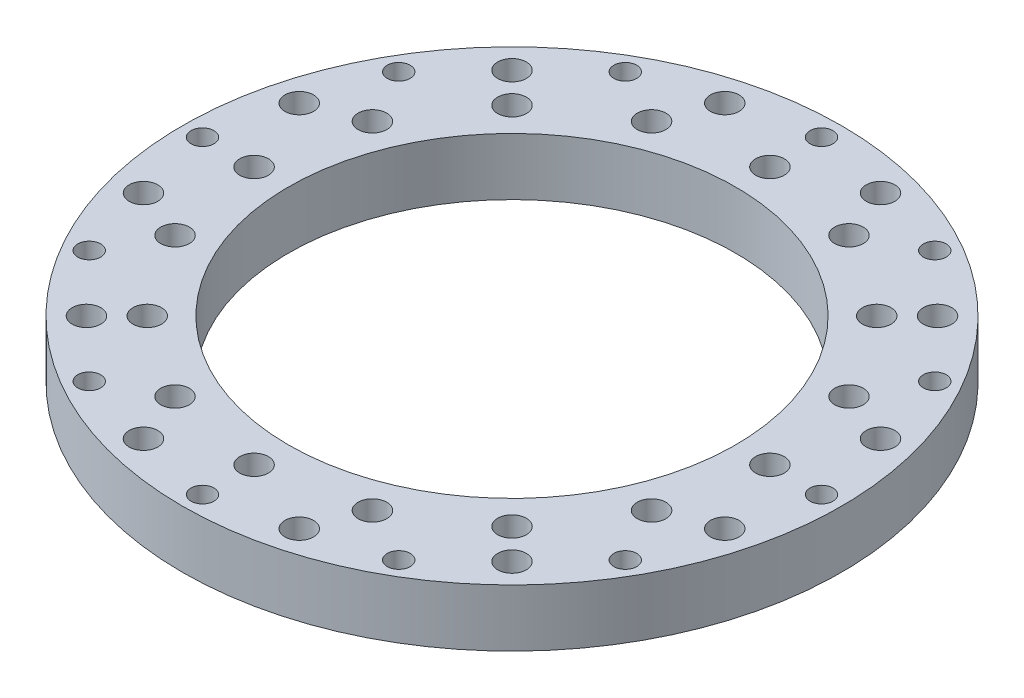
SolidWorks part; units mm, degrees
ref_plane "Front Plane" through (0, 0, 0) normal (0, 0, 1) x (1, 0, 0)
ref_plane "Top Plane" through (0, 0, 0) normal (0, 1, 0) x (1, 0, 0)
ref_plane "Right Plane" through (0, 0, 0) normal (1, 0, 0) x (0, 0, -1)
sketch "Sketch1" plane through (0, 0, 0) normal (0, 1, 0) x (1, 0, 0)
  line L0 (0, 0) -> (0, 52.5) construction
  line L1 (0, 0) -> (13.588, 50.7111) construction
  circle A12 centre (0, 0) radius 39
  circle A13 centre (0, 0) radius 57.5
  circle A14 centre (0, 0) radius 54 construction
  circle A15 centre (0, 54) radius 2
  circle A16 centre (27, 46.7654) radius 2
  circle A17 centre (46.7654, 27) radius 2
  circle A18 centre (54, 0) radius 2
  circle A19 centre (46.7654, -27) radius 2
  circle A20 centre (27, -46.7654) radius 2
  circle A21 centre (0, -54) radius 2
  circle A22 centre (-27, -46.7654) radius 2
  circle A23 centre (-46.7654, -27) radius 2
  circle A24 centre (-54, 0) radius 2
  circle A25 centre (-46.7654, 27) radius 2
  circle A26 centre (-27, 46.7654) radius 2
  circle A27 centre (0, 0) radius 52.5 construction
  circle A34 centre (13.588, 50.7111) radius 2.5
  circle A35 centre (37.1231, 37.1231) radius 2.5
  circle A36 centre (50.7111, 13.588) radius 2.5
  circle A37 centre (50.7111, -13.588) radius 2.5
  circle A38 centre (37.1231, -37.1231) radius 2.5
  circle A39 centre (13.588, -50.7111) radius 2.5
  circle A40 centre (-13.588, -50.7111) radius 2.5
  circle A41 centre (-37.1231, -37.1231) radius 2.5
  circle A42 centre (-50.7111, -13.588) radius 2.5
  circle A43 centre (-50.7111, 13.588) radius 2.5
  circle A44 centre (-37.1231, 37.1231) radius 2.5
  circle A45 centre (-13.588, 50.7111) radius 2.5
  point P21 (0, 0)
  point P28 (0, 0)
  point P56 (0, 0)
  point P60 (0, 0)
  dimension "D1" = 105
  dimension "D2" = 15
  dimension "D4" = 115
  dimension "D5" = 78
  dimension "D6" = 108
  dimension "D7" = 4
  dimension "D3" = 5
  dimension "D8" = 12
extrude "Boss-Extrude1" add sketch "Sketch1" along normal blind 10
sketch "Sketch2" plane through (0, 10, 0) normal (0, 1, 0) x (1, 0, 0)
  circle A0 centre (0, 0) radius 45 construction
  circle A1 centre (0, 45) radius 2.5
  circle A2 centre (17.2208, 41.5746) radius 2.5
  circle A3 centre (31.8198, 31.8198) radius 2.5
  circle A4 centre (41.5746, 17.2208) radius 2.5
  circle A5 centre (45, 0) radius 2.5
  circle A6 centre (41.5746, -17.2208) radius 2.5
  circle A7 centre (31.8198, -31.8198) radius 2.5
  circle A8 centre (17.2208, -41.5746) radius 2.5
  circle A9 centre (0, -45) radius 2.5
  circle A10 centre (-17.2208, -41.5746) radius 2.5
  circle A11 centre (-31.8198, -31.8198) radius 2.5
  circle A12 centre (-41.5746, -17.2208) radius 2.5
  circle A13 centre (-45, 0) radius 2.5
  circle A14 centre (-41.5746, 17.2208) radius 2.5
  circle A15 centre (-31.8198, 31.8198) radius 2.5
  circle A16 centre (-17.2208, 41.5746) radius 2.5
  point P27 (0, 0)
  dimension "D1" = 90
  dimension "D2" = 5
  dimension "D3" = 16
extrude "Cut-Extrude1" cut sketch "Sketch2" against normal blind 10
sketch "Sketch4" plane through (0, 0, 0) normal (0, 1, 0) x (1, 0, 0)
  circle A0 centre (0, 0) radius 45 construction
  circle A1 centre (0, 45) radius 5
  circle A2 centre (0, 45) radius 2.5
  circle A3 centre (17.2208, 41.5746) radius 2.5
  circle A4 centre (31.8198, 31.8198) radius 2.5
  circle A5 centre (41.5746, 17.2208) radius 2.5
  circle A6 centre (45, 0) radius 2.5
  circle A7 centre (41.5746, -17.2208) radius 2.5
  circle A8 centre (31.8198, -31.8198) radius 2.5
  circle A9 centre (17.2208, -41.5746) radius 2.5
  circle A10 centre (0, -45) radius 2.5
  circle A11 centre (-17.2208, -41.5746) radius 2.5
  circle A12 centre (-31.8198, -31.8198) radius 2.5
  circle A13 centre (17.2208, 41.5746) radius 5
  circle A14 centre (31.8198, 31.8198) radius 5
  circle A15 centre (41.5746, 17.2208) radius 5
  circle A16 centre (45, 0) radius 5
  circle A17 centre (41.5746, -17.2208) radius 5
  circle A18 centre (31.8198, -31.8198) radius 5
  circle A19 centre (17.2208, -41.5746) radius 5
  circle A20 centre (0, -45) radius 5
  circle A21 centre (-17.2208, -41.5746) radius 5
  circle A22 centre (-31.8198, -31.8198) radius 5
  circle A23 centre (-41.5746, -17.2208) radius 5
  circle A24 centre (-45, 0) radius 5
  circle A25 centre (-41.5746, 17.2208) radius 5
  circle A26 centre (-31.8198, 31.8198) radius 5
  circle A27 centre (-17.2208, 41.5746) radius 5
  circle A28 centre (-41.5746, -17.2208) radius 2.5
  circle A29 centre (-45, 0) radius 2.5
  circle A30 centre (-41.5746, 17.2208) radius 2.5
  circle A31 centre (-31.8198, 31.8198) radius 2.5
  circle A32 centre (-17.2208, 41.5746) radius 2.5
  point P29 (0, 0)
  point P50 (0, 0)
  dimension "D1" = 10
  dimension "D2" = 16
  dimension "D3" = 16
extrude "Boss-Extrude3" add sketch "Sketch4" against normal blind 0.4
